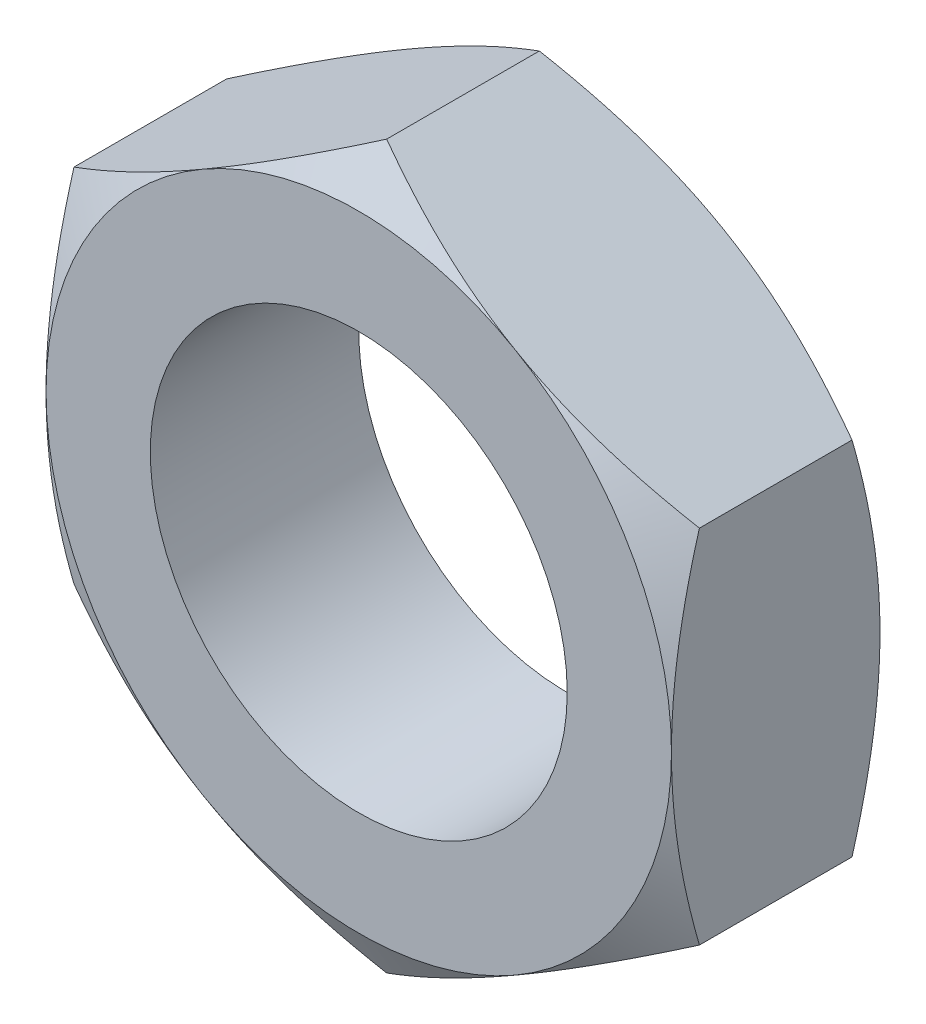
SolidWorks part; units mm, degrees
material "1.4000 (X6Cr13)"
ref_plane "Płaszczyzna przednia" through (0, 0, 0) normal (0, 0, 1) x (1, 0, 0)
ref_plane "Płaszczyzna górna" through (0, 0, 0) normal (0, 1, 0) x (1, 0, 0)
ref_plane "Płaszczyzna prawa" through (0, 0, 0) normal (1, 0, 0) x (0, 0, -1)
sketch "Szkic1" plane through (0, 0, 0) normal (0, 0, 1) x (1, 0, 0)
  line L1 (-12, 6.9282) -> (-12, -6.9282)
  line L2 (-12, -6.9282) -> (0, -13.8564)
  line L3 (0, -13.8564) -> (12, -6.9282)
  line L4 (12, -6.9282) -> (12, 6.9282)
  line L5 (12, 6.9282) -> (0, 13.8564)
  line L6 (0, 13.8564) -> (-12, 6.9282)
  circle A0 centre (0, 0) radius 8
  circle A1 centre (0, 0) radius 12 construction
  dimension "d" = 16
  dimension "s" = 24
extrude "Dodanie-wyciągnięcie1" add sketch "Szkic1" along normal mid plane 8
sketch "Szkic2" plane through (0, 0, 4) normal (0, 0, 1) x (1, 0, 0)
  circle A0 centre (0, 0) radius 12
  dimension "D1" = 24
extrude "Wytnij-wyciągnięcie2" cut sketch "Szkic2" against normal blind 8 draft 60 flip side to cut
mirror "Lustro1" about plane through (0, 0, 0) normal (0, 0, 1) of "Wytnij-wyciągnięcie2"
equation "\"D1@Szkic2\" = \"s@Szkic1\""
equation "\"D1@Wytnij-wyciągnięcie2\" = \"m@Dodanie-wyciągnięcie1\""
